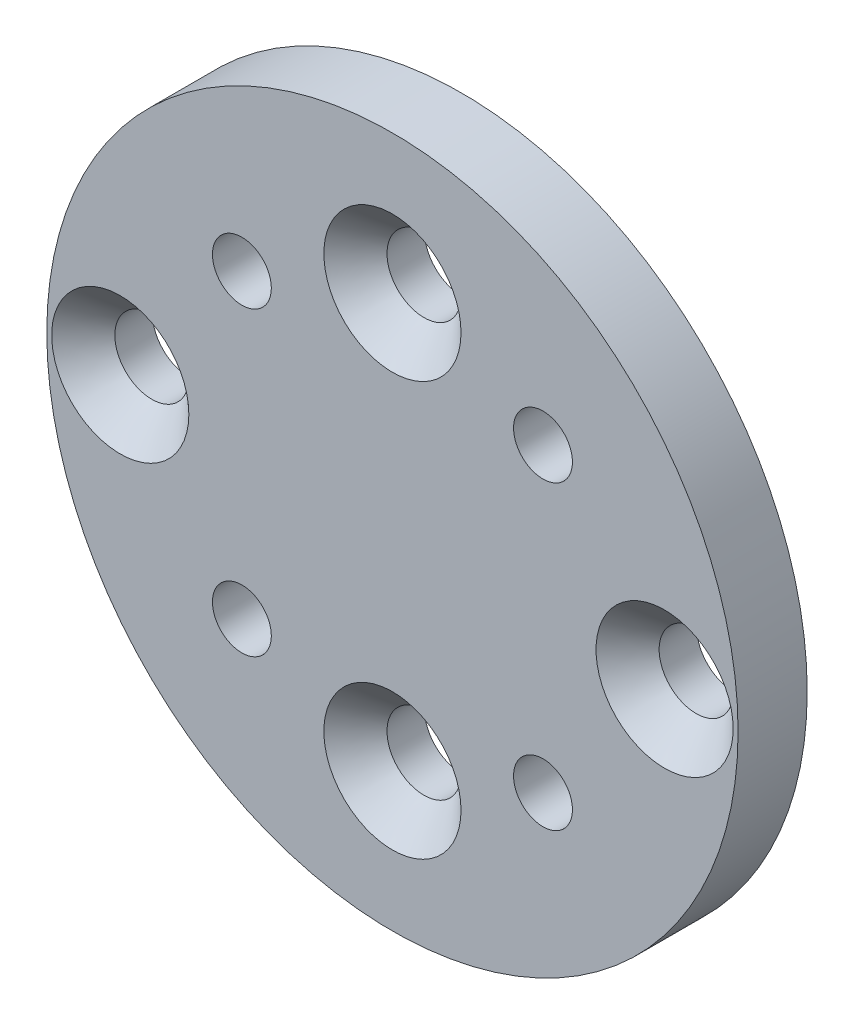
SolidWorks part; units mm, degrees
ref_plane "Front Plane" through (0, 0, 0) normal (0, 0, 1) x (1, 0, 0)
ref_plane "Top Plane" through (0, 0, 0) normal (0, 1, 0) x (1, 0, 0)
ref_plane "Right Plane" through (0, 0, 0) normal (1, 0, 0) x (0, 0, -1)
sketch "Sketch1" plane through (0, 0, 0) normal (0, 0, 1) x (1, 0, 0)
  circle A0 centre (0, 0) radius 15.875
  dimension "D1" = 31.75
extrude "Boss-Extrude1" add sketch "Sketch1" along normal blind 3.175
hole_wizard "CSK for M3 Flat Head Machine Screw1" positions "Sketch3" profile "Sketch2" countersink size "M3" standard "ANSI Metric" end condition through all
sketch "Sketch3" plane through (0, 0, 3.175) normal (0, 0, 1) x (1, 0, 0)
  line L0 (-12.5, 0) -> (12.5, 0) construction
  line L3 (0, 9.5) -> (0, -9.5) construction
  point P0 (0, 9.5)
  point P2 (0, -9.5)
  point P4 (12.5, 0)
  point P6 (-12.5, 0)
  dimension "D1" = 19
  dimension "D2" = 25
sketch "Sketch2" plane through (0, 9.5, 3.175) normal (1, 0, 0) x (0, -1, 0)
  line L0 (0, 0) -> (0, 3.175)
  line L1 (0, 3.175) -> (1.7, 3.175)
  line L2 (1.7, 3.175) -> (1.7, 1.45)
  line L3 (1.7, 1.45) -> (3.15, 0)
  line L5 (3.15, 0) -> (0, 0)
  line L6 (-1.7, 1.45) -> (-3.15, 0) construction
  line L11 (0, -6.35) -> (0, 107.95) construction
  dimension "Thru Hole Dia." = 3.4
  dimension "Thru Hole Depth" = 3.175
  dimension "Near C'Sink Dia." = 6.3
  dimension "Near C'Sink Angle" = 90
hole_wizard "#6-32 Tapped Hole1" positions "Sketch5" profile "Sketch4" tap size "#6-32" standard "ANSI Inch" end condition through all
sketch "Sketch5" plane through (0, 0, 3.175) normal (0, 0, 1) x (1, 0, 0)
  line L0 (-6.9148, 6.9148) -> (6.9148, -6.9148) construction
  line L3 (6.9148, 6.9148) -> (-6.9148, -6.9148) construction
  point P0 (-6.9148, 6.9148)
  point P2 (6.9148, 6.9148)
  point P4 (6.9148, -6.9148)
  point P6 (-6.9148, -6.9148)
  dimension "D1" = 19.558
sketch "Sketch4" plane through (-6.9148, 6.9148, 3.175) normal (1, 0, 0) x (0, -1, 0)
  line L0 (0, 0) -> (0, 3.175)
  line L1 (0, 3.175) -> (1.3525, 3.175)
  line L2 (1.3525, 3.175) -> (1.3525, 0)
  line L5 (1.3525, 0) -> (0, 0)
  line L11 (0, -6.35) -> (0, 107.95) construction
  dimension "Thread Major Dia." = 2.7051
  dimension "Thru Tap Drill Depth" = 3.175
